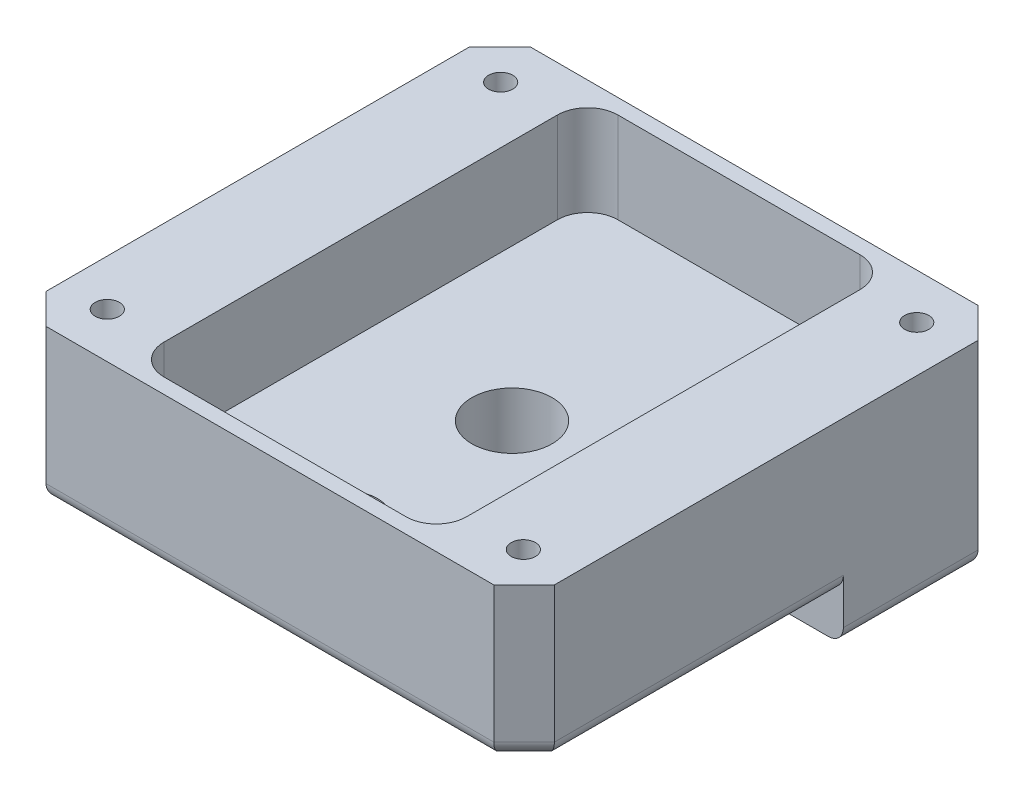
SolidWorks part; units mm, degrees
ref_plane "Front Plane" through (0, 0, 0) normal (0, 0, 1) x (1, 0, 0)
ref_plane "Top Plane" through (0, 0, 0) normal (0, 1, 0) x (1, 0, 0)
ref_plane "Right Plane" through (0, 0, 0) normal (1, 0, 0) x (0, 0, -1)
sketch "Skizze1" plane through (0, 0, 0) normal (0, 1, 0) x (1, 0, 0)
  line L1 (-16.8, 16) -> (16.8, 16)
  line L2 (-16.8, 16) -> (-16.8, -16)
  line L3 (-16.8, -16) -> (16.8, -16)
  line L4 (16.8, 16) -> (16.8, -16)
  line L5 (0, -16) -> (0, 16) construction
  line L6 (-16.8, 0) -> (16.8, 0) construction
  point P204 (0, 0)
  dimension "D1" = 33.6
  dimension "D2" = 32
extrude "Aufsatz-Linear austragen1" add sketch "Skizze1" along normal blind 13
sketch "Skizze17" plane through (0, 13, 0) normal (0, 1, 0) x (1, 0, 0)
  line L1 (-10, 15) -> (10, 15)
  line L2 (-10, 15) -> (-10, -15)
  line L3 (-10, -15) -> (10, -15)
  line L4 (10, 15) -> (10, -15)
  line L5 (0, -15) -> (0, 15) construction
  line L6 (-10, 0) -> (10, 0) construction
  point P300 (0, 0)
  dimension "D1" = 20
  dimension "D2" = 30
extrude "Schnitt-Linear austragen2" cut sketch "Skizze17" against normal blind 6
hole_wizard "Kernloch für M2 Gewinde1" positions "Skizze18" profile "Skizze19" hole size "M2" standard "DIN" end condition through all
sketch "Skizze18" plane through (0, 13, 0) normal (0, 1, 0) x (1, 0, 0)
  line L0 (0, 16) -> (0, -16) construction
  line L1 (16.8, 16) -> (-16.8, 16) construction
  line L2 (-16.8, -16) -> (16.8, -16) construction
  line L5 (-16.8, 0) -> (16.8, 0) construction
  line L6 (-16.8, 16) -> (-16.8, -16) construction
  line L7 (16.8, -16) -> (16.8, 16) construction
  point P0 (-13.75, 13)
  point P2 (13.75, 13)
  point P4 (13.75, -13)
  point P6 (-13.75, -13)
  dimension "D1" = 27.5
  dimension "D2" = 26
sketch "Skizze19" plane through (-13.75, 13, -13) normal (1, 0, 0) x (0, 0, 1)
  line L0 (0, 0) -> (0, 13)
  line L1 (0, 13) -> (0.8, 13)
  line L2 (0.8, 13) -> (0.8, 0)
  line L5 (0.8, 0) -> (0, 0)
  line L11 (0, -6.35) -> (0, 107.95) construction
  dimension "Bohrerdurchmesser" = 1.6
  dimension "Bohrungstiefe" = 13
fillet "Verrundung2" radius 2 4 edges at (-10, 10, 15) (10, 10, -15) (10, 10, 15) (-10, 10, -15)
hole_wizard "Durchgangsloch für M52" positions "Skizze20" profile "Skizze22" hole size "M5" standard "DIN" end condition through all
sketch "Skizze20" plane through (0, 7, 0) normal (0, 1, 0) x (1, 0, 0)
  point P0 (0, 0)
sketch "Skizze22" plane through (0, 7, 0) normal (1, 0, 0) x (0, 0, 1)
  line L0 (0, 0) -> (0, 7)
  line L1 (0, 7) -> (2.65, 7)
  line L2 (2.65, 7) -> (2.65, 0)
  line L5 (2.65, 0) -> (0, 0)
  line L11 (0, -6.35) -> (0, 107.95) construction
  dimension "Bohrerdurchmesser" = 5.3
  dimension "Bohrungstiefe" = 7
hole_wizard "Ø3.0mm Clearance Stiftloch1" positions "Skizze23" profile "Skizze24" hole size "Ø3.0" standard "DIN"
sketch "Skizze23" plane through (0, 0, 0) normal (0, -1, 0) x (-1, 0, 0)
  line L0 (-16.8, 0) -> (16.8, 0) construction
  line L1 (-16.8, -16) -> (-16.8, 16) construction
  line L2 (16.8, 16) -> (16.8, -16) construction
  point P0 (-9.5, 0)
  dimension "D1" = 9.5
sketch "Skizze24" plane through (9.5, 0, 0) normal (1, 0, 0) x (0, 0, -1)
  line L0 (0, 0) -> (0, 5.9013)
  line L1 (0, 5.9013) -> (1.5, 5)
  line L2 (1.5, 5) -> (1.5, 0)
  line L5 (1.5, 0) -> (0, 0)
  line L10 (0, 5.9013) -> (-1.5, 5) construction
  line L11 (0, -6.35) -> (0, 107.95) construction
  dimension "Bohrerdurchmesser" = 3
  dimension "Bohrungstiefe" = 5
  dimension "Spitzenwinkel" = 118
hole_wizard "Kernloch für M5 Gewinde1" positions "Skizze25" profile "Skizze26" hole size "M5" standard "DIN" end condition up to next
sketch "Skizze25" plane through (0, 0, 0) normal (0, -1, 0) x (-1, 0, 0)
  line L0 (0, 16) -> (0, -16) construction
  line L1 (-16.8, 16) -> (16.8, 16) construction
  line L2 (16.8, -16) -> (-16.8, -16) construction
  point P0 (0, -11)
  dimension "D1" = 11
sketch "Skizze26" plane through (0, 0, 11) normal (1, 0, 0) x (0, 0, -1)
  line L0 (0, 0) -> (0, 7)
  line L1 (0, 7) -> (2.1, 7)
  line L2 (2.1, 7) -> (2.1, 0)
  line L5 (2.1, 0) -> (0, 0)
  line L11 (0, -6.35) -> (0, 107.95) construction
  dimension "Bohrerdurchmesser" = 4.2
  dimension "Bohrungstiefe" = 7
sketch "Skizze27" plane through (0, 0, 0) normal (0, -1, 0) x (1, 0, 0)
  line L0 (16.8, 16) -> (16.8, -16) construction
  line L1 (-16.8, -5.1) -> (16.8, -5.1)
  line L2 (-16.8, -5.1) -> (-16.8, 16)
  line L3 (-16.8, 16) -> (16.8, 16)
  line L4 (16.8, -5.1) -> (16.8, 16)
  line L5 (-16.8, 16) -> (16.8, 16) construction
  line L6 (-16.8, -16) -> (-16.8, 16) construction
  point P0 (0, 0)
  dimension "D2" = 5.1
extrude "Schnitt-Linear austragen3" cut sketch "Skizze27" against normal blind 3
hole_wizard "M5 Gewindebohrung2" [suppressed] positions "Skizze28" profile "Skizze29" tap size "M5" standard "DIN"
sketch "Skizze28" plane through (16.8, 0, 0) normal (1, 0, 0) x (0, 0, -1)
  line L4 (13, 7) -> (-13, 7) construction
  line L9 (-16, 9.5) -> (16, 9.5) construction
  line L10 (-16, 13) -> (-16, 3) construction
  line L11 (16, 13) -> (16, 0) construction
  point P0 (0, 9.5)
  dimension "D1" = 2.5
sketch "Skizze29" plane through (16.8, 9.5, 0) normal (0, 1, 0) x (0, 0, -1)
  line L0 (0, 0) -> (0, 6.8)
  line L1 (0, 6.8) -> (2.1, 6.8)
  line L2 (2.1, 6.8) -> (2.1, 0)
  line L5 (2.1, 0) -> (0, 0)
  line L11 (0, -6.35) -> (0, 107.95) construction
  dimension "Bohrerdurchmesser" = 4.2
  dimension "Bohrungstiefe" = 6.8
cosmetic thread "Bohrungsgewinde14" [suppressed] parameters "D2"=5
chamfer "Fase1" distance 2 angle 45 4 edges at (-16.8, 8, 16) (16.8, 8, 16) (16.8, 6.5, -16) (-16.8, 6.5, -16)
fillet "Verrundung3" radius 1 10 edges at (15.8, 3, 15) (-15.8, 3, 15) (-15.8, 0, -15) (15.8, 0, -15) (16.8, 0, -9.55) (16.8, 3, 4.45) (0, 3, 16) (-16.8, 3, 4.45) (-16.8, 0, -9.55) (0, 0, -16)
